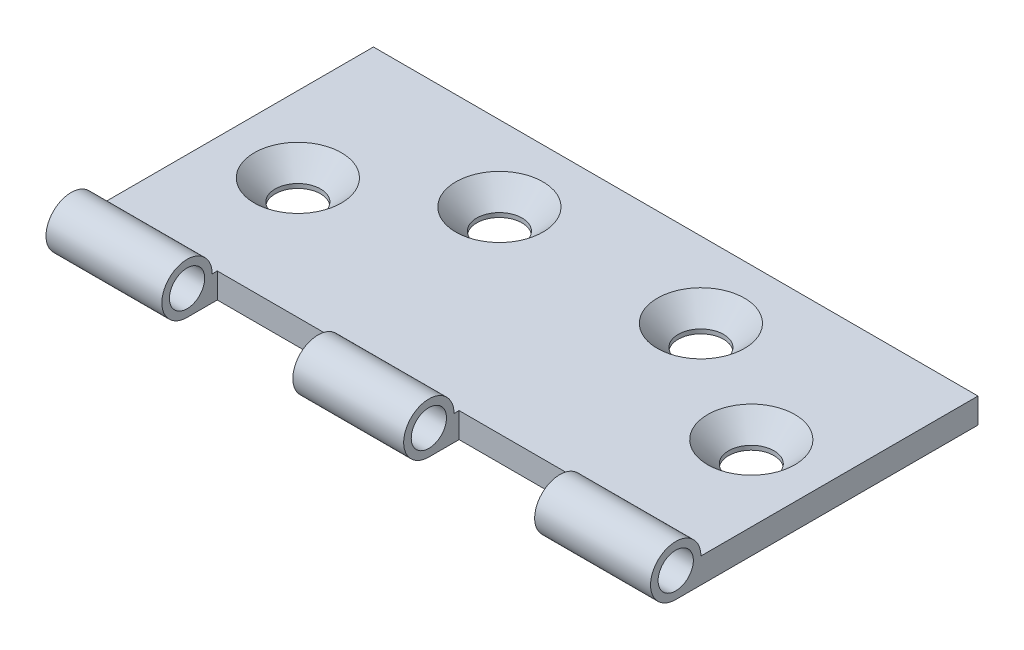
SolidWorks part; units mm, degrees
ref_plane "Ebene vorne" through (0, 0, 0) normal (1, 0, 0) x (0, 1, 0)
ref_plane "Ebene oben" through (0, 0, 0) normal (0, 0, 1) x (0, 1, 0)
ref_plane "Ebene rechts" through (0, 0, 0) normal (0, 1, 0) x (-1, 0, 0)
sketch "Skizze1" plane through (0, 0, 0) normal (1, 0, 0) x (0, 1, 0)
  line L0 (0, 0) -> (0, 60)
  dimension "D1" = 60
extrude "Linear-Austragen-Dünn1" add sketch "Skizze1" along normal mid plane 120 thin
sketch "Skizze2" plane through (60, 0, 0) normal (1, 0, 0) x (0, 1, 0)
  circle A0 centre (5, 60) radius 5
sweep "Austragung1" add profiles "Skizze2" path edge at (0, 5, 60)
sketch "Skizze3" plane through (60, 0, 0) normal (1, 0, 0) x (0, 1, 0)
  line L0 (5, 55) -> (5, 65) construction
  arc A0 (5, 55) -> (0, 60) centre (5, 60) ccw construction
  circle A1 centre (5, 60) radius 3.5
extrude "Schnitt-Linear austragen1" cut sketch "Skizze3" against normal through all
sketch "Skizze6" plane through (0, 5, 0) normal (0, 1, 0) x (1, 0, 0)
  line L0 (60, 0) -> (60, -55) construction
  line L1 (60, 0) -> (-60, 0) construction
  point P0 (45, -30)
  point P2 (20, -15)
  dimension "D1" = 15
  dimension "D2" = 40
  dimension "D3" = 15
  dimension "D4" = 30
hole_wizard "Formsenkung für M8 Linsensenkschraube1" positions "Skizze6" profile "Skizze5" countersink size "M8" standard "ANSI Metric" end condition through all
sketch "Skizze5" plane through (45, 5, 30) normal (1, 0, 0) x (0, 0, 1)
  line L0 (0, 0) -> (0, 5)
  line L1 (0, 5) -> (4.5, 5)
  line L2 (4.5, 5) -> (4.5, 4.15)
  line L3 (4.5, 4.15) -> (8.65, 0)
  line L5 (8.65, 0) -> (0, 0)
  line L6 (-4.5, 4.15) -> (-8.65, 0) construction
  line L11 (0, -6.35) -> (0, 107.95) construction
  dimension "Bohrerdurchmesser" = 9
  dimension "Bohrungstiefe" = 5
  dimension "Senkdurchmesser (Oben)" = 17.3
  dimension "Senkwinkel (Oben)" = 90
mirror "Spiegeln1" about plane through (0, 0, 0) normal (1, 0, 0) of "Formsenkung für M8 Linsensenkschraube1"
sketch "Layout für Schnitte" plane through (0, 5, 0) normal (0, 1, 0) x (-1, 0, 0)
  line L1 (60, 55) -> (60, 65) construction
  line L2 (-60, 54) -> (60, 54)
  line L3 (-60, 54) -> (60, 54)
  line L4 (-60, 65) -> (-60, 55) construction
  line L5 (60, 54) -> (60, 65)
  line L6 (-60, 65) -> (-60, 54)
  line L7 (-60, 65) -> (60, 65)
  line L8 (-36, 65) -> (-36, 54)
  line L9 (-12, 65) -> (-12, 54)
  line L10 (0, 5.5) -> (0, -5.5) construction
  line L11 (12, 65) -> (12, 54)
  line L12 (36, 65) -> (36, 54)
  dimension "D2" = 24
  dimension "D3" = 24
  dimension "D1" = 1
sketch "Skizze10" plane through (0, 5, 0) normal (0, 1, 0) x (-1, 0, 0)
  line L0 (-60, 54) -> (60, 54) construction
  line L2 (-60, 65) -> (60, 65) construction
  line L4 (-37, 54) -> (-11, 54)
  line L6 (-37, 65) -> (-11, 65)
  line L10 (-11, 65) -> (-11, 54)
  line L11 (-37, 65) -> (-37, 54)
  line L12 (-37, 65) -> (-37, 54)
  line L14 (37, 65) -> (37, 54)
  line L15 (37, 65) -> (37, 54)
  line L16 (-11, 65) -> (-11, 54)
  line L17 (11, 54) -> (37, 54)
  line L18 (11, 65) -> (11, 54)
  line L19 (11, 65) -> (11, 54)
  line L20 (11, 65) -> (37, 65)
  dimension "D1" = 1
  dimension "D2" = 1
  dimension "D3" = 1
  dimension "D4" = 1
extrude "2Cut" cut sketch "Skizze10" against normal through all both and the other way through all
sketch "Skizze9" plane through (0, 5, 0) normal (0, 1, 0) x (-1, 0, 0)
  line L0 (-60, 54) -> (60, 54) construction
  line L1 (60, 54) -> (60, 65) construction
  line L2 (-60, 65) -> (60, 65) construction
  line L3 (-60, 65) -> (-60, 54) construction
  line L4 (-60, 54) -> (-35, 54)
  line L5 (60, 54) -> (60, 65)
  line L6 (-60, 65) -> (-35, 65)
  line L7 (-60, 65) -> (-60, 54)
  line L8 (37, 54) -> (60, 54)
  line L9 (-13, 54) -> (13, 54)
  line L10 (-35, 65) -> (-35, 54)
  line L11 (-35, 65) -> (-35, 54)
  line L12 (-13, 65) -> (13, 65)
  line L13 (37, 65) -> (37, 54)
  line L14 (37, 65) -> (37, 54)
  line L16 (-13, 65) -> (-13, 54)
  line L17 (-13, 65) -> (-13, 54)
  line L18 (37, 65) -> (60, 65)
  line L19 (13, 65) -> (13, 54)
  line L20 (13, 65) -> (13, 54)
  dimension "D1" = 1
  dimension "D2" = 1
  dimension "D3" = 1
  dimension "D4" = 1
extrude "3Cut" [suppressed] cut sketch "Skizze9" against normal through all both and the other way through all
equation "\"D4@Skizze6\"= \"D1@Skizze1\" / 2"
equation "\"D2@Skizze6\"= \"D1@Linear-Austragen-Dünn1\" / 3"
equation "\"D2@Layout für Schnitte\" = \"D1@Linear-Austragen-Dünn1\" / 5"
equation "\"D3@Layout für Schnitte\" = \"D1@Linear-Austragen-Dünn1\" / 5"
